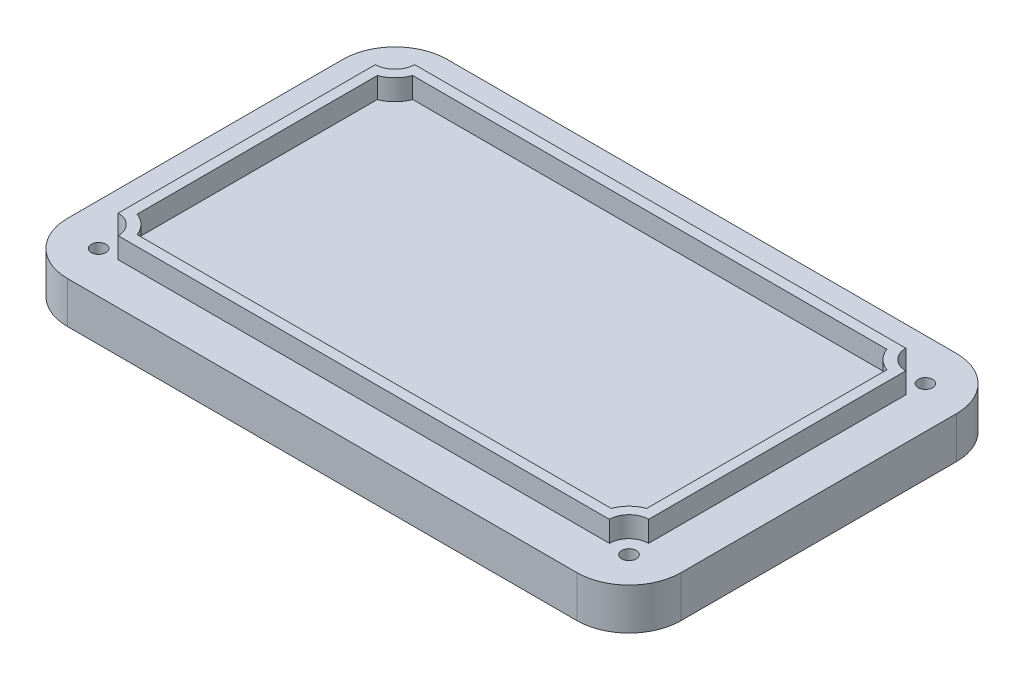
SolidWorks part; units mm, degrees
ref_plane "Front Plane" through (0, 0, 0) normal (0, 0, 1) x (1, 0, 0)
ref_plane "Top Plane" through (0, 0, 0) normal (0, 1, 0) x (1, 0, 0)
ref_plane "Right Plane" through (0, 0, 0) normal (1, 0, 0) x (0, 0, -1)
sketch "Sketch1" plane through (0, 0, 0) normal (0, 1, 0) x (1, 0, 0)
  line B0 (-43.8284, -28.5) -> (43.8284, -28.5)
  line B1 (51, -21.3284) -> (51, 21.3284)
  line B2 (43.8284, 28.5) -> (-43.8284, 28.5)
  line B3 (-51, 21.3284) -> (-51, -21.3284)
  line B4 (-59, 26.5) -> (-59, -26.5)
  line B5 (-49, -36.5) -> (49, -36.5)
  line B6 (59, -26.5) -> (59, 26.5)
  line B7 (49, 36.5) -> (-49, 36.5)
  line B8 (-47.2349, -28.5) -> (47.2349, -28.5)
  line B9 (51, -24.7349) -> (51, 24.7349)
  line B10 (-51, 24.7349) -> (-51, -24.7349)
  line B11 (47.2349, 28.5) -> (-47.2349, 28.5)
  arc B12 (51, -21.3284) -> (43.8284, -28.5) centre (51, -28.5) ccw
  arc B13 (43.8284, 28.5) -> (51, 21.3284) centre (51, 28.5) ccw
  arc B14 (-51, 21.3284) -> (-43.8284, 28.5) centre (-51, 28.5) ccw
  arc B15 (-43.8284, -28.5) -> (-51, -21.3284) centre (-51, -28.5) ccw
  arc B16 (-49, 36.5) -> (-59, 26.5) centre (-49, 26.5) ccw
  arc B17 (-59, -26.5) -> (-49, -36.5) centre (-49, -26.5) ccw
  arc B18 (49, -36.5) -> (59, -26.5) centre (49, -26.5) ccw
  arc B19 (59, 26.5) -> (49, 36.5) centre (49, 26.5) ccw
  circle B20 centre (-51, 28.5) radius 1.4
  circle B21 centre (-51, -28.5) radius 1.4
  circle B22 centre (51, -28.5) radius 1.4
  circle B23 centre (51, 28.5) radius 1.4
  arc B24 (51, -24.7349) -> (47.2349, -28.5) centre (51, -28.5) ccw
  arc B25 (-51, 24.7349) -> (-47.2349, 28.5) centre (-51, 28.5) ccw
  arc B26 (-47.2349, -28.5) -> (-51, -24.7349) centre (-51, -28.5) ccw
  arc B27 (47.2349, 28.5) -> (51, 24.7349) centre (51, 28.5) ccw
sketch_block_instance "Block-BlockLon-1"
sketch_block "Block-BlockLon"
extrude "Boss-Extrude1" add sketch "Sketch1" along normal blind 8 contours B6 B19 B7 B16 B4 B17 B5 B18 B23 B22 B21 B20 B11 B27 B9 B1 B24 B8 B0 B26 B10 B3 B25 B2
sketch "Sketch2" plane through (0, 8, 0) normal (0, 1, 0) x (1, 0, 0)
  line L1 (51, -24.7349) -> (51, 24.7349) construction
  line L3 (-47.2349, -28.5) -> (47.2349, -28.5) construction
  line L4 (59, -26.5) -> (59, 26.5)
  line L5 (49, 36.5) -> (-49, 36.5)
  line L6 (-59, 26.5) -> (-59, -26.5)
  line L7 (-49, -36.5) -> (49, -36.5)
  line L8 (59, -26.5) -> (59, 26.5)
  line L9 (49, 36.5) -> (-49, 36.5)
  line L10 (-59, 26.5) -> (-59, -26.5)
  line L11 (-49, -36.5) -> (49, -36.5)
  line L12 (-51, 24.7349) -> (-51, -24.7349) construction
  line L13 (47.2349, 28.5) -> (-47.2349, 28.5) construction
  line L14 (51, -24.7349) -> (51, 24.7349)
  line L15 (-47.2349, -28.5) -> (47.2349, -28.5)
  line L16 (-51, 24.7349) -> (-51, -24.7349)
  line L17 (47.2349, 28.5) -> (-47.2349, 28.5)
  arc A0 (47.2349, 28.5) -> (51, 24.7349) centre (51, 28.5) ccw construction
  arc A1 (51, -24.7349) -> (47.2349, -28.5) centre (51, -28.5) ccw construction
  arc A2 (-47.2349, -28.5) -> (-51, -24.7349) centre (-51, -28.5) ccw construction
  arc A3 (-51, 24.7349) -> (-47.2349, 28.5) centre (-51, 28.5) ccw construction
  arc A4 (59, 26.5) -> (49, 36.5) centre (49, 26.5) ccw
  arc A5 (-49, 36.5) -> (-59, 26.5) centre (-49, 26.5) ccw
  arc A6 (-59, -26.5) -> (-49, -36.5) centre (-49, -26.5) ccw
  arc A7 (49, -36.5) -> (59, -26.5) centre (49, -26.5) ccw
  arc A8 (59, 26.5) -> (49, 36.5) centre (49, 26.5) ccw
  arc A9 (-49, 36.5) -> (-59, 26.5) centre (-49, 26.5) ccw
  arc A10 (-59, -26.5) -> (-49, -36.5) centre (-49, -26.5) ccw
  arc A11 (49, -36.5) -> (59, -26.5) centre (49, -26.5) ccw
  arc A12 (47.2349, 28.5) -> (51, 24.7349) centre (51, 28.5) ccw
  arc A13 (51, -24.7349) -> (47.2349, -28.5) centre (51, -28.5) ccw
  arc A14 (-47.2349, -28.5) -> (-51, -24.7349) centre (-51, -28.5) ccw
  arc A15 (-51, 24.7349) -> (-47.2349, 28.5) centre (-51, 28.5) ccw
  dimension "D1" = 0
extrude "Boss-Extrude2" add sketch "Sketch2" against normal blind 8 separate body contours A12 L14 A13 L15 A14 L16 A15 L17
sketch "Sketch3" plane through (0, 8, 0) normal (0, 1, 0) x (1, 0, 0)
  line L0 (51, -24.7349) -> (51, 24.7349) construction
  line L1 (-47.2349, -28.5) -> (47.2349, -28.5) construction
  line L2 (-51, 24.7349) -> (-51, -24.7349) construction
  line L3 (47.2349, 28.5) -> (-47.2349, 28.5) construction
  line L4 (51, -24.7349) -> (51, 24.7349)
  line L5 (-47.2349, -28.5) -> (47.2349, -28.5)
  line L6 (-51, 24.7349) -> (-51, -24.7349)
  line L7 (47.2349, 28.5) -> (-47.2349, 28.5)
  line L8 (45.593, 26.5) -> (-45.593, 26.5)
  line L9 (-49, 23.093) -> (-49, -23.093)
  line L10 (-45.593, -26.5) -> (45.593, -26.5)
  line L11 (49, -23.093) -> (49, 23.093)
  line L12 (47.2349, 26.5) -> (-47.2349, 26.5) construction
  line L13 (-49, 24.7349) -> (-49, -24.7349) construction
  line L14 (49, -24.7349) -> (49, 24.7349) construction
  line L15 (-47.2349, -26.5) -> (47.2349, -26.5) construction
  arc A0 (47.2349, 28.5) -> (51, 24.7349) centre (51, 28.5) ccw construction
  arc A1 (51, -24.7349) -> (47.2349, -28.5) centre (51, -28.5) ccw construction
  arc A2 (-47.2349, -28.5) -> (-51, -24.7349) centre (-51, -28.5) ccw construction
  arc A3 (-51, 24.7349) -> (-47.2349, 28.5) centre (-51, 28.5) ccw construction
  arc A4 (47.2349, 28.5) -> (51, 24.7349) centre (51, 28.5) ccw
  arc A5 (51, -24.7349) -> (47.2349, -28.5) centre (51, -28.5) ccw
  arc A6 (-47.2349, -28.5) -> (-51, -24.7349) centre (-51, -28.5) ccw
  arc A7 (-51, 24.7349) -> (-47.2349, 28.5) centre (-51, 28.5) ccw
  arc A8 (-49, 23.093) -> (-45.2349, 28.5) centre (-51, 28.5) ccw
  arc A9 (-45.593, -26.5) -> (-49, -23.093) centre (-51, -28.5) ccw
  arc A10 (49, -23.093) -> (45.593, -26.5) centre (51, -28.5) ccw
  arc A11 (45.593, 26.5) -> (49, 23.093) centre (51, 28.5) ccw
  arc A12 (-51, 22.7349) -> (-45.2349, 28.5) centre (-51, 28.5) ccw construction
  arc A13 (45.2349, 28.5) -> (51, 22.7349) centre (51, 28.5) ccw construction
  arc A14 (51, -22.7349) -> (45.2349, -28.5) centre (51, -28.5) ccw construction
  arc A15 (-45.2349, -28.5) -> (-51, -22.7349) centre (-51, -28.5) ccw construction
  dimension "D1" = 2
  dimension "D2" = 2
  dimension "D3" = 2
  dimension "D4" = 2
  dimension "D5" = 2
  dimension "D6" = 2
  dimension "D7" = 2
  dimension "D8" = 2
extrude "Boss-Extrude3" add sketch "Sketch3" along normal blind 4
sketch "Sketch4" plane through (0, 0, 0) normal (0, -1, 0) x (1, 0, 0)
  line L0 (0, 0) -> (0, 29.7701) construction
  line L1 (0, 0) -> (-28.6253, 0) construction
  circle A0 centre (-51, 28.5) radius 3.5
  circle A1 centre (51, 28.5) radius 3.5
  circle A2 centre (51, -28.5) radius 3.5
  circle A3 centre (-51, -28.5) radius 3.5
  dimension "D1" = 7
extrude "Cut-Extrude1" cut sketch "Sketch4" against normal blind 3
